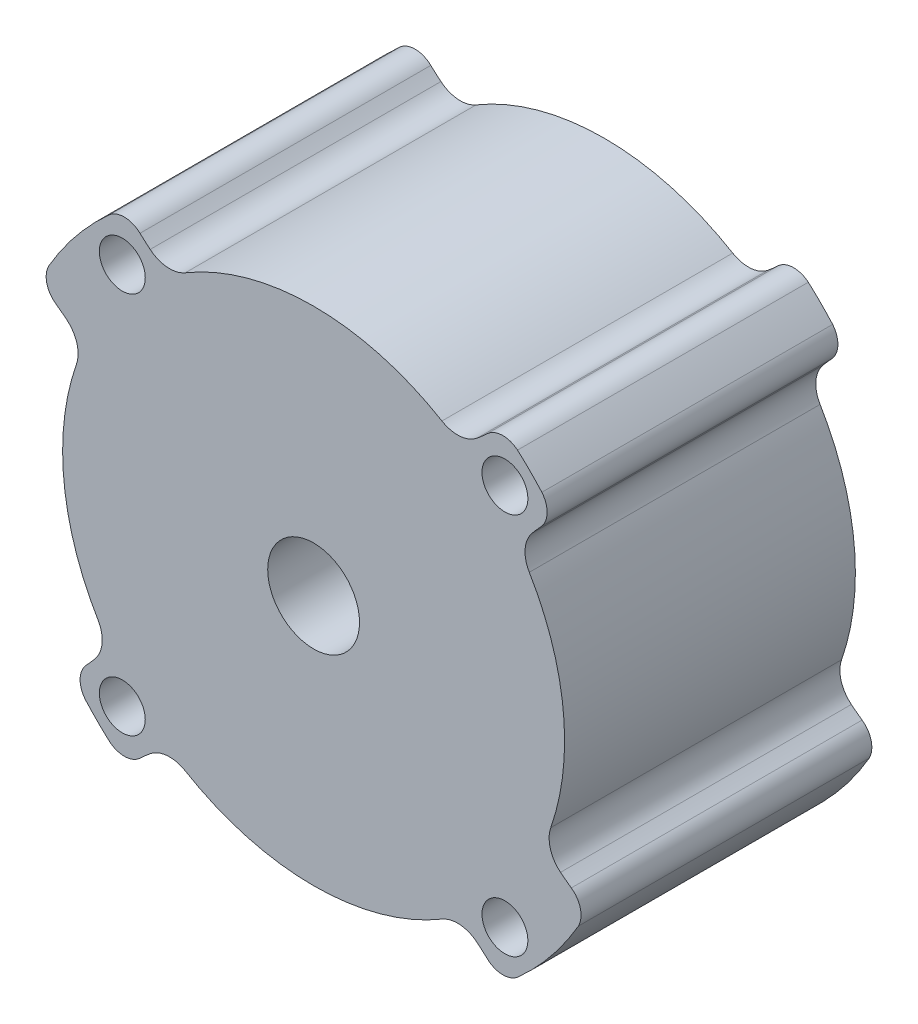
SolidWorks part; units mm, degrees
material "Gray Cast Iron"
ref_plane "Front Plane" through (0, 0, 0) normal (0, 0, 1) x (1, 0, 0)
ref_plane "Top Plane" through (0, 0, 0) normal (0, 1, 0) x (1, 0, 0)
ref_plane "Right Plane" through (0, 0, 0) normal (1, 0, 0) x (0, 0, -1)
sketch "Sketch1" plane through (0, 0, 0) normal (0, 0, 1) x (1, 0, 0)
  line L0 (64.8354, 10.4258) -> (77.3354, -2.0742) construction
  line L1 (61.8284, 10.5564) -> (77.3354, -2.0742) construction
  line L2 (64.8354, -14.5742) -> (89.8354, 10.4258) construction
  line L3 (77.3354, -2.0742) -> (77.3354, 14.3258) construction
  circle A0 centre (77.3354, -2.0742) radius 3
  arc A1 (61.8362, 3.2863) -> (63.2414, -10.4598) centre (77.3354, -2.0742) ccw
  arc A2 (85.721, 12.0198) -> (68.9498, 12.0198) centre (77.3354, -2.0742) ccw
  circle A3 centre (89.8354, 10.4258) radius 1.5
  circle A4 centre (64.8354, 10.4258) radius 1.5
  circle A5 centre (89.8354, -14.5742) radius 1.5
  circle A6 centre (64.8354, -14.5742) radius 1.5
  arc A7 (66.6553, 12.1951) -> (68.9498, 12.0198) centre (67.9272, 13.7386) ccw
  arc A8 (65.9927, 12.778) -> (64.0113, 12.8412) centre (64.9661, 11.6843) ccw
  arc A9 (92.8346, -7.4347) -> (91.4294, 6.3114) centre (77.3354, -2.0742) ccw
  arc A10 (65.9927, 12.778) -> (66.6553, 12.1951) centre (75.3514, 22.748) ccw
  arc A11 (90.6595, -16.9896) -> (94.6382, -12.1049) centre (77.3354, -2.0742) ccw
  arc A12 (92.2508, 11.2499) -> (90.6595, 12.8412) centre (77.3354, -2.0742) ccw
  arc A13 (61.2002, 5.4979) -> (61.8362, 3.2863) centre (59.9461, 3.94) cw
  arc A14 (60.4954, 6.0288) -> (61.2002, 5.4979) centre (52.6252, -5.1536) cw
  arc A15 (60.4954, 6.0288) -> (60.0326, 7.9565) centre (61.3587, 7.2554) cw
  arc A16 (88.0155, 12.1951) -> (85.721, 12.0198) centre (86.7436, 13.7386) cw
  arc A17 (88.678, 12.778) -> (88.0155, 12.1951) centre (79.3194, 22.748) cw
  arc A18 (88.678, 12.778) -> (90.6595, 12.8412) centre (89.7046, 11.6843) cw
  arc A19 (92.1876, 9.2684) -> (92.2508, 11.2499) centre (91.0939, 10.295) ccw
  arc A20 (92.1876, 9.2684) -> (91.6047, 8.6059) centre (102.1576, -0.0902) ccw
  arc A21 (91.6047, 8.6059) -> (91.4294, 6.3114) centre (93.1482, 7.334) ccw
  arc A22 (66.6553, -16.3436) -> (68.9498, -16.1683) centre (67.9272, -17.887) cw
  arc A23 (65.9927, -16.9264) -> (66.6553, -16.3436) centre (75.3514, -26.8964) cw
  arc A24 (65.9927, -16.9264) -> (64.0113, -16.9896) centre (64.9661, -15.8328) cw
  arc A25 (62.4832, -13.4169) -> (62.42, -15.3983) centre (63.5769, -14.4435) ccw
  arc A26 (62.4832, -13.4169) -> (63.066, -12.7544) centre (52.5132, -4.0582) ccw
  arc A27 (63.066, -12.7544) -> (63.2414, -10.4598) centre (61.5226, -11.4825) ccw
  arc A28 (88.0155, -16.3436) -> (85.721, -16.1683) centre (86.7436, -17.887) ccw
  arc A29 (88.678, -16.9264) -> (88.0155, -16.3436) centre (79.3194, -26.8964) ccw
  arc A30 (88.678, -16.9264) -> (90.6595, -16.9896) centre (89.7046, -15.8328) ccw
  arc A31 (94.1754, -10.1772) -> (94.6382, -12.1049) centre (93.312, -11.4039) cw
  arc A32 (94.1754, -10.1772) -> (93.4705, -9.6463) centre (102.0456, 1.0051) cw
  arc A33 (93.4705, -9.6463) -> (92.8346, -7.4347) centre (94.7247, -8.0884) cw
  arc A34 (64.0113, 12.8412) -> (60.0326, 7.9565) centre (77.3354, -2.0742) ccw
  arc A35 (62.42, -15.3983) -> (64.0113, -16.9896) centre (77.3354, -2.0742) ccw
  arc A36 (68.9498, -16.1683) -> (85.721, -16.1683) centre (77.3354, -2.0742) ccw
  dimension "D1" = 32.8
  dimension "D2" = 6
  dimension "D3" = 40
  dimension "D4" = 1.5
  dimension "D5" = 13.6743
  dimension "D6" = 2
  dimension "D7" = 3
  dimension "D8" = 25
  dimension "D9" = 12.5
  dimension "D10" = 25
  dimension "D11" = 12.5
  dimension "D12" = 6.3
extrude "Saliente-Extruir1" add sketch "Sketch1" along normal blind 19
sketch "Croquis1" plane through (0, 0, 0) normal (0, 0, -1) x (-1, 0, 0)
  circle A0 centre (-77.3354, -2.0742) radius 12.5
  dimension "D1" = 25
extrude "Cortar-Extruir1" cut sketch "Croquis1" against normal blind 2.5
equation "\"D9@Sketch1\"=\"D8@Sketch1\"/2"
equation "\"D11@Sketch1\"=\"D10@Sketch1\"/2"
